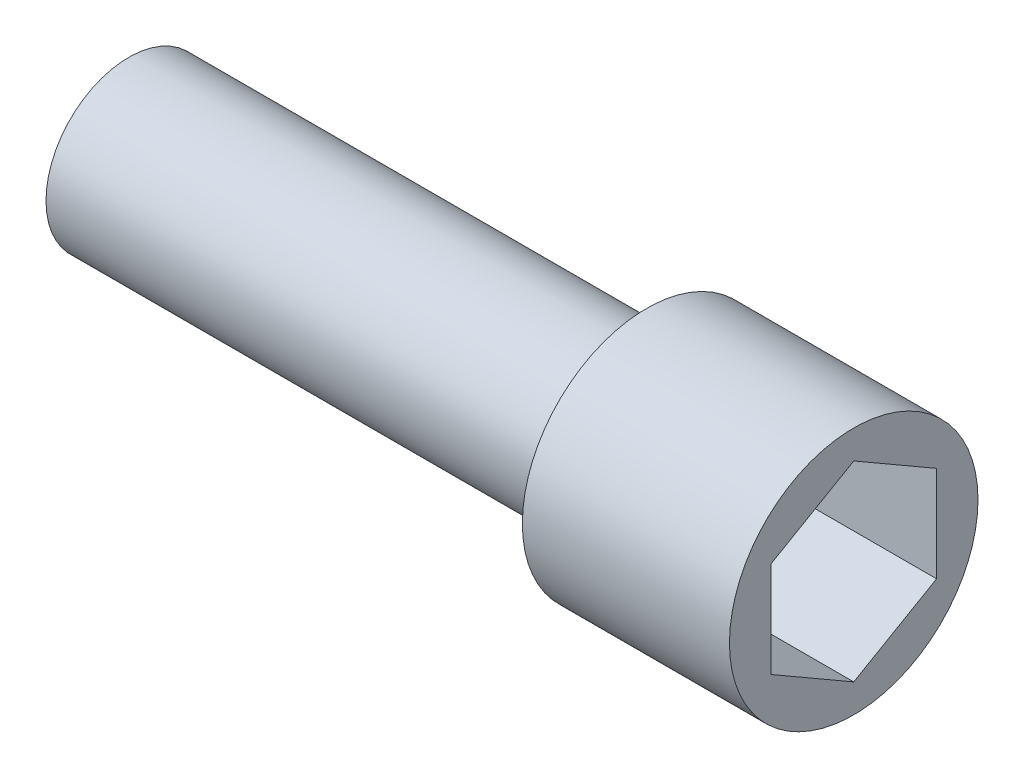
SolidWorks part; units mm, degrees
ref_plane "Front Plane" through (0, 0, 0) normal (1, 0, 0) x (0, 1, 0)
ref_plane "Top Plane" through (0, 0, 0) normal (0, 0, 1) x (0, 1, 0)
ref_plane "Right Plane" through (0, 0, 0) normal (0, 1, 0) x (-1, 0, 0)
sketch "Sketch1" plane through (0, 0, 0) normal (1, 0, 0) x (0, 1, 0)
  circle A0 centre (0, 0) radius 6
  dimension "D1" = 12
extrude "Boss-Extrude1" add sketch "Sketch1" along normal blind 10
sketch "Sketch2" plane through (10, 0, 0) normal (1, 0, 0) x (0, 1, 0)
  line L1 (4.6188, 0) -> (2.3094, 4)
  line L2 (2.3094, 4) -> (-2.3094, 4)
  line L3 (-2.3094, 4) -> (-4.6188, 0)
  line L4 (-4.6188, 0) -> (-2.3094, -4)
  line L5 (-2.3094, -4) -> (2.3094, -4)
  line L6 (2.3094, -4) -> (4.6188, 0)
  circle A0 centre (0, 0) radius 4 construction
  dimension "D1" = 8
extrude "Cut-Extrude1" cut sketch "Sketch2" against normal blind 7
sketch "Sketch3" plane through (0, 0, 0) normal (-1, 0, 0) x (0, -1, 0)
  circle A0 centre (0, 0) radius 4
  dimension "D1" = 8
extrude "Boss-Extrude2" add sketch "Sketch3" along normal blind 25
